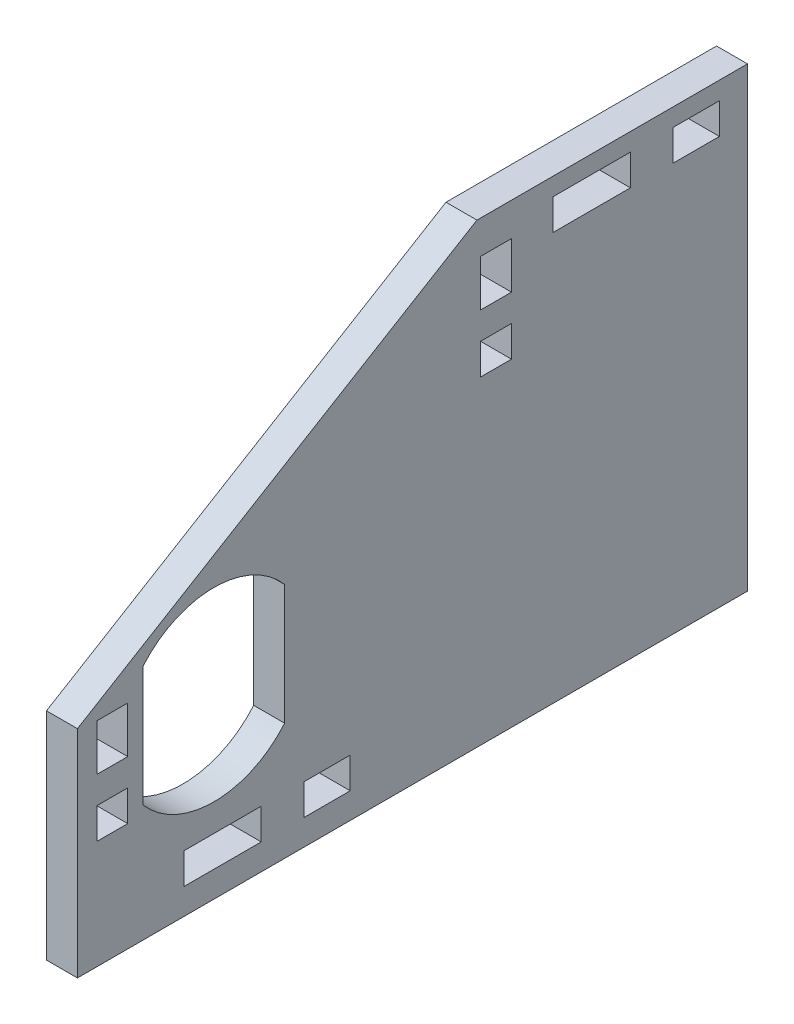
SolidWorks part; units mm, degrees
ref_plane "Front Plane" through (0, 0, 0) normal (0, 0, 1) x (1, 0, 0)
ref_plane "Top Plane" through (0, 0, 0) normal (0, 1, 0) x (1, 0, 0)
ref_plane "Right Plane" through (0, 0, 0) normal (1, 0, 0) x (0, 0, -1)
sketch "Sketch1" plane through (0, 0, 0) normal (1, 0, 0) x (0, 0, -1)
  line L0 (16.3304, 31.234) -> (26.3304, 31.234)
  line L1 (-45.1266, -21.4659) -> (41.4624, -21.4659)
  line L2 (-45.1266, -21.4659) -> (-45.1266, 6.4371)
  line L3 (6.4978, 37.5389) -> (41.4624, 37.5389)
  line L4 (41.4624, -21.4659) -> (41.4624, 37.5389)
  line L5 (-42.6266, 6.0625) -> (-38.6266, 6.0625)
  line L6 (-42.6266, 6.0625) -> (-42.6266, 0.0625)
  line L7 (-42.6266, 0.0625) -> (-38.6266, 0.0625)
  line L8 (-38.6266, 6.0625) -> (-38.6266, 0.0625)
  line L9 (-42.6266, -3.4375) -> (-38.6266, -3.4375)
  line L10 (-42.6266, -3.4375) -> (-42.6266, -7.4375)
  line L11 (-42.6266, -7.4375) -> (-38.6266, -7.4375)
  line L12 (-38.6266, -3.4375) -> (-38.6266, -7.4375)
  line L13 (-31.3747, -18.1111) -> (-21.3747, -18.1111)
  line L14 (-31.3747, -18.1111) -> (-31.3747, -14.1111)
  line L15 (-31.3747, -14.1111) -> (-21.3747, -14.1111)
  line L16 (-21.3747, -18.1111) -> (-21.3747, -14.1111)
  line L17 (-15.8748, -14.1425) -> (-9.8748, -14.1425)
  line L18 (-15.8748, -14.1425) -> (-15.8748, -18.1425)
  line L19 (-15.8748, -18.1425) -> (-9.8748, -18.1425)
  line L20 (-9.8748, -14.1425) -> (-9.8748, -18.1425)
  line L21 (16.3304, 31.234) -> (16.3304, 35.234)
  line L22 (16.3304, 35.234) -> (26.3304, 35.234)
  line L23 (26.3304, 31.234) -> (26.3304, 35.234)
  line L24 (31.8304, 35.234) -> (37.8304, 35.234)
  line L25 (31.8304, 35.234) -> (31.8304, 31.234)
  line L26 (31.8304, 31.234) -> (37.8304, 31.234)
  line L27 (37.8304, 35.234) -> (37.8304, 31.234)
  line L28 (6.9637, 33.2423) -> (10.9637, 33.2423)
  line L29 (6.9637, 33.2423) -> (6.9637, 27.2423)
  line L30 (6.9637, 27.2423) -> (10.9637, 27.2423)
  line L31 (10.9637, 33.2423) -> (10.9637, 27.2423)
  line L32 (6.9637, 23.7423) -> (10.9637, 23.7423)
  line L33 (6.9637, 23.7423) -> (6.9637, 19.7423)
  line L34 (6.9637, 19.7423) -> (10.9637, 19.7423)
  line L35 (10.9637, 23.7423) -> (10.9637, 19.7423)
  line L36 (-45.1266, 6.4371) -> (6.4978, 37.5389)
  line L38 (-21.3747, -14.1111) -> (-15.8748, -14.1425) construction
  line L39 (26.3304, 35.234) -> (31.8304, 35.234) construction
  line L40 (6.9637, 27.2423) -> (6.9637, 23.7423) construction
  line L41 (-42.6266, 6.0625) -> (-45.1266, 6.0625) construction
  line L43 (-36.6522, -6.3395) -> (-36.6522, 9.1882)
  line L45 (-18.3522, -6.3395) -> (-18.3522, 9.1882)
  line L46 (-28.6502, -0.2134) -> (-26.3542, 3.062) construction
  line L47 (-28.6502, 3.062) -> (-26.3542, -0.2134) construction
  arc A0 (-36.6522, -6.3395) -> (-18.3522, -6.3395) centre (-27.5022, 1.4243) ccw
  circle A6 centre (-27.5022, 1.4243) radius 2 construction
  arc A14 (-18.3522, 9.1882) -> (-36.6522, 9.1882) centre (-27.5022, 1.4243) ccw
extrude "Boss-Extrude1" add sketch "Sketch1" along normal blind 4
